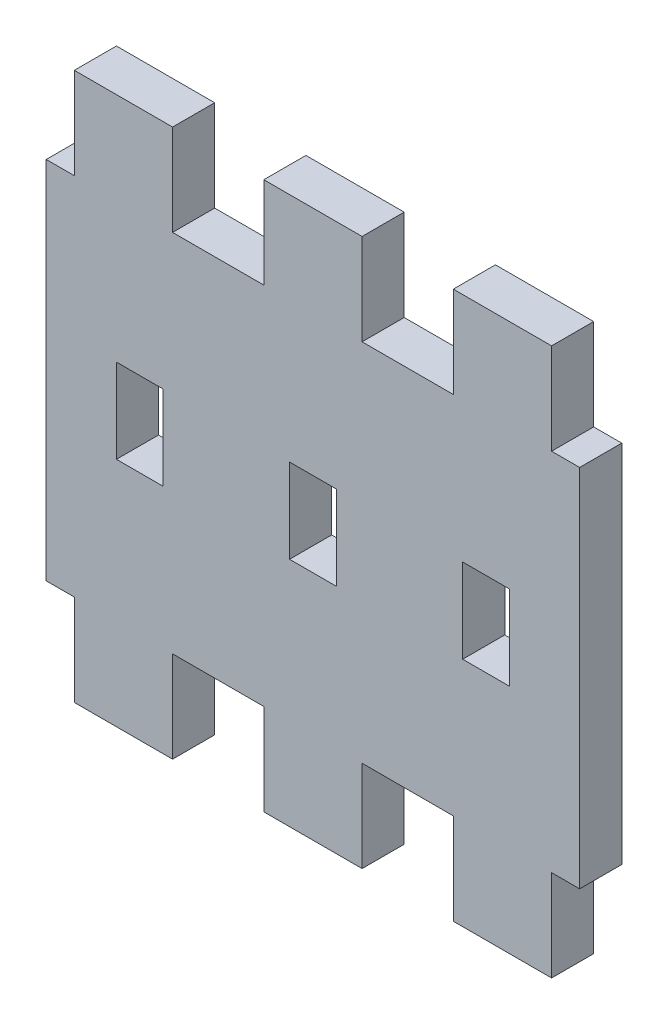
SolidWorks part; units mm, degrees
ref_plane "前视基准面" through (0, 0, 0) normal (0, 0, 1) x (1, 0, 0)
ref_plane "上视基准面" through (0, 0, 0) normal (0, 1, 0) x (1, 0, 0)
ref_plane "右视基准面" through (0, 0, 0) normal (1, 0, 0) x (0, 0, -1)
sketch "草图1" plane through (0, 0, 0) normal (0, 0, 1) x (1, 0, 0)
  line L0 (-17, 13) -> (-10, 13)
  line L1 (-19, 13) -> (19, 13)
  line L2 (-19, 13) -> (-19, -13)
  line L3 (-19, -13) -> (19, -13)
  line L4 (19, 13) -> (19, -13)
  line L5 (0, -13) -> (0, 13) construction
  line L6 (-19, 0) -> (19, 0) construction
  line L7 (-17, 13) -> (-17, 19.5)
  line L8 (-10, 13) -> (-10, 19.5)
  line L9 (-17, 19.5) -> (-10, 19.5)
  line L10 (-3.5, 13) -> (3.5, 13)
  line L11 (-3.5, 13) -> (-3.5, 19.5)
  line L12 (3.5, 13) -> (3.5, 19.5)
  line L13 (-3.5, 19.5) -> (3.5, 19.5)
  line L14 (10, 13) -> (17, 13)
  line L15 (10, 13) -> (10, 19.5)
  line L16 (17, 13) -> (17, 19.5)
  line L17 (10, 19.5) -> (17, 19.5)
  line L18 (10, -19.5) -> (17, -19.5)
  line L19 (17, -13) -> (17, -19.5)
  line L20 (10, -13) -> (10, -19.5)
  line L21 (10, -13) -> (17, -13)
  line L22 (-3.5, -19.5) -> (3.5, -19.5)
  line L23 (3.5, -13) -> (3.5, -19.5)
  line L24 (-3.5, -13) -> (-3.5, -19.5)
  line L25 (-3.5, -13) -> (3.5, -13)
  line L26 (-17, -19.5) -> (-10, -19.5)
  line L27 (-10, -13) -> (-10, -19.5)
  line L28 (-17, -13) -> (-17, -19.5)
  line L29 (-17, -13) -> (-10, -13)
  line L31 (-1.6667, 3) -> (1.6667, 3)
  line L32 (-1.6667, 3) -> (-1.6667, -3)
  line L33 (-1.6667, -3) -> (1.6667, -3)
  line L34 (1.6667, 3) -> (1.6667, -3)
  line L35 (0, -3) -> (0, 3) construction
  line L36 (-1.6667, 0) -> (1.6667, 0) construction
  line L37 (-14, 3) -> (-10.6667, 3)
  line L38 (-14, 3) -> (-14, -3)
  line L39 (-14, -3) -> (-10.6667, -3)
  line L40 (-10.6667, 3) -> (-10.6667, -3)
  line L41 (-12.3333, -3) -> (-12.3333, 3) construction
  line L42 (-14, 0) -> (-10.6667, 0) construction
  line L43 (10.6667, 3) -> (14, 3)
  line L44 (10.6667, 3) -> (10.6667, -3)
  line L45 (10.6667, -3) -> (14, -3)
  line L46 (14, 3) -> (14, -3)
  line L47 (12.3333, -3) -> (12.3333, 3) construction
  line L48 (10.6667, 0) -> (14, 0) construction
  point P0 (0, 0)
  point P28 (0, 0)
  point P32 (-12.3333, 0)
  point P36 (12.3333, 0)
  dimension "D1" = 6.5
  dimension "D2" = 6.5
  dimension "D3" = 6.5
  dimension "D4" = 2
  dimension "D5" = 2
  dimension "D6" = 7
  dimension "D7" = 26
  dimension "D8" = 9
  dimension "D9" = 9
  dimension "D10" = 5
  dimension "D11" = 10
extrude "凸台-拉伸1" add sketch "草图1" along normal blind 3 contours L3 L24 L22 L23 | L3 L28 L26 L27 | L3 L20 L18 L19 | L4 L1 L0 L2 L3 L31 L34 L33 L32 L37 L40 L39 L38 L43 L46 L45 L44 | L13 L12 L10 L11 | L17 L16 L14 L15
